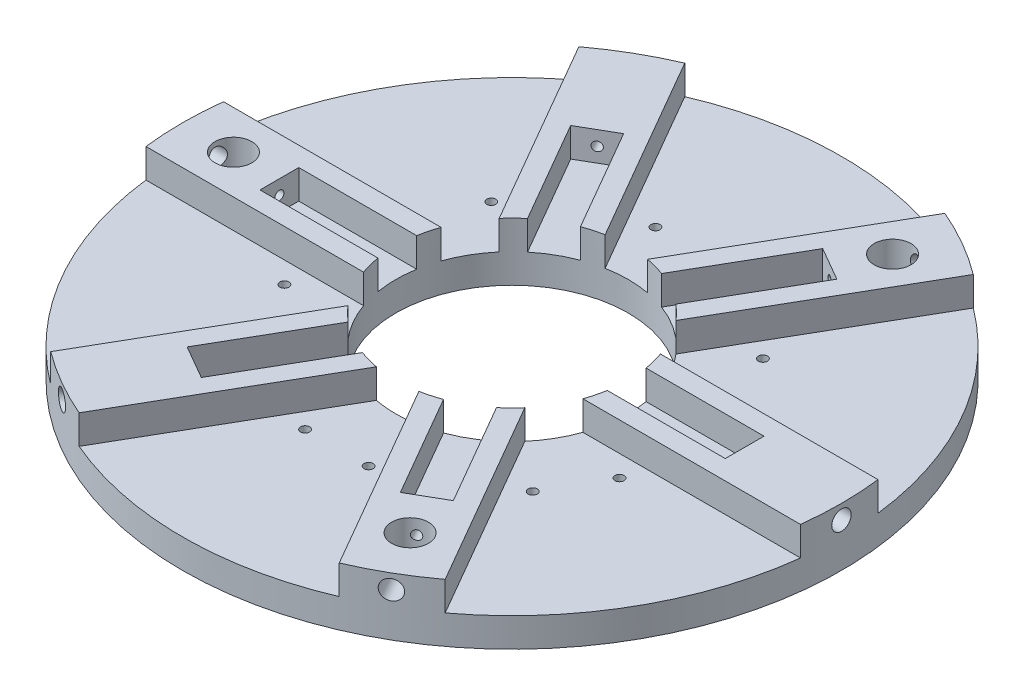
SolidWorks part; units mm, degrees
ref_plane "Front Plane" through (0, 0, 0) normal (0, 0, 1) x (1, 0, 0)
ref_plane "Top Plane" through (0, 0, 0) normal (0, 1, 0) x (1, 0, 0)
ref_plane "Right Plane" through (0, 0, 0) normal (1, 0, 0) x (0, 0, -1)
sketch "Sketch1" plane through (0, 0, 0) normal (0, 1, 0) x (1, 0, 0)
  circle A0 centre (0, 0) radius 43.18
extrude "Boss-Extrude1" add sketch "Sketch1" along normal blind 7.62 contours A0
hole_wizard "#97 (0.0059) Diameter Hole1" positions "Sketch5" profile "Sketch4" hole size "#97" standard "ANSI Inch"
sketch "Sketch5" plane through (0, 7.62, 0) normal (0, 1, 0) x (1, 0, 0)
  point P0 (0, 0)
sketch "Sketch4" plane through (0, 7.62, 0) normal (1, 0, 0) x (0, 0, 1)
  line L0 (0, 0) -> (0, 34.5571)
  line L1 (0, 34.5571) -> (15.24, 25.4)
  line L2 (15.24, 25.4) -> (15.24, 0)
  line L5 (15.24, 0) -> (0, 0)
  line L10 (0, 34.5571) -> (-15.24, 25.4) construction
  line L11 (0, -6.35) -> (0, 107.95) construction
  dimension "Hole Dia." = 30.48
  dimension "Hole Depth" = 25.4
  dimension "Drill Angle" = 118
hole_wizard "CBORE for #00 Binding Head Machine Screw1" positions "Sketch7" profile "Sketch6" counterbore size "#00" standard "ANSI Inch" end condition through all
sketch "Sketch7" plane through (0, 7.62, 0) normal (0, 1, 0) x (1, 0, 0)
  point P0 (-36.4998, 0)
sketch "Sketch6" plane through (-36.4998, 7.62, 0) normal (1, 0, 0) x (0, 0, 1)
  line L0 (0, 0) -> (0, 7.62)
  line L1 (0, 7.62) -> (1.27, 7.62)
  line L3 (1.27, 7.62) -> (1.27, 6.35)
  line L4 (1.27, 6.35) -> (2.413, 6.35)
  line L5 (2.413, 6.35) -> (2.413, 0)
  line L7 (2.413, 0) -> (0, 0)
  line L11 (0, -6.35) -> (0, 107.95) construction
  dimension "Thru Hole Dia." = 2.54
  dimension "Thru Hole Depth" = 7.62
  dimension "C'Bore Dia." = 4.826
  dimension "C'Bore Depth" = 6.35
pattern_circular "CirPattern1" count 3 over 360 about axis through (0, 0, 0) along (0, 1, 0) of "CBORE for #00 Binding Head Machine Screw1"
sketch "Sketch8" plane through (0, 7.62, 0) normal (0, 1, 0) x (1, 0, 0)
  line L0 (-14.3684, -5.08) -> (-42.8801, -5.08)
  line L1 (-11.5836, -9.9034) -> (-25.8395, -34.5953)
  arc A0 (-14.3684, -5.08) -> (-11.5836, -9.9034) centre (0, 0) ccw
  circle A1 centre (0, 0) radius 15.24 construction
  circle A2 centre (0, 0) radius 43.18 construction
  arc A3 (-42.8801, -5.08) -> (-25.8395, -34.5953) centre (0, 0) ccw
extrude "Cut-Extrude1" cut sketch "Sketch8" against normal blind 3.81
sketch "Sketch9" plane through (0, 7.62, 0) normal (0, 1, 0) x (1, 0, 0)
  line L0 (0, 0) -> (0, 2.54)
  line L1 (0, 2.54) -> (-30.48, 2.54)
  line L2 (-30.48, 2.54) -> (-30.48, -2.54)
  line L3 (-30.48, -2.54) -> (0, -2.54)
  line L4 (0, -2.54) -> (0, 0)
extrude "Cut-Extrude2" cut sketch "Sketch9" against normal blind 3.81
pattern_circular "CirPattern2" count 6 over 360 about axis through (0, 0, 0) along (0, 1, 0) of "Cut-Extrude1", "Cut-Extrude2"
ref_plane "Plane1" through (-42.8801, 0, 0) normal (1, 0, 0) x (0, 0, -1)
ref_plane "Plane2" through (-44.1501, 0, 0) normal (1, 0, 0) x (0, 0, -1)
hole_wizard "#97 (0.0059) Diameter Hole2" positions "Sketch11" profile "Sketch10" hole size "#97" standard "ANSI Inch"
sketch "Sketch11" plane through (-44.1501, 0, 0) normal (1, 0, 0) x (0, 0, -1)
  point P0 (0, 5.715)
sketch "Sketch10" plane through (-44.1501, 5.715, 0) normal (0, 1, 0) x (0, 0, 1)
  line L0 (0, 0) -> (0, 8.89)
  line L1 (0, 8.89) -> (1.27, 8.89)
  line L2 (1.27, 8.89) -> (1.27, 0)
  line L5 (1.27, 0) -> (0, 0)
  line L10 (0, 8.89) -> (-1.27, 8.89) construction
  line L11 (0, -6.35) -> (0, 107.95) construction
  dimension "Hole Dia." = 2.54
  dimension "Hole Depth" = 8.89
  dimension "Drill Angle" = 180
hole_wizard "#0-80 Tapped Hole2" positions "Sketch13" profile "Sketch12" tap size "#0-80" standard "ANSI Inch"
sketch "Sketch13" plane through (-44.1501, 0, 0) normal (1, 0, 0) x (0, 0, -1)
  point P0 (0, 5.715)
sketch "Sketch12" plane through (-44.1501, 5.715, 0) normal (0, 1, 0) x (0, 0, 1)
  line L0 (0, 0) -> (0, 21.9479)
  line L1 (0, 21.9479) -> (0.5956, 21.59)
  line L2 (0.5956, 21.59) -> (0.5956, 0)
  line L5 (0.5956, 0) -> (0, 0)
  line L10 (0, 21.9479) -> (-0.5956, 21.59) construction
  line L11 (0, -6.35) -> (0, 107.95) construction
  dimension "Tap Drill Dia." = 1.1913
  dimension "Tap Drill Depth" = 21.59
  dimension "Drill Angle" = 118
cosmetic thread "Hole Thread1" parameters "D1"=3.6815, "D2"=1.524
pattern_circular "CirPattern3" count 6 over 360 about axis through (0, 0, 0) along (0, 1, 0) of "#97 (0.0059) Diameter Hole2", "#0-80 Tapped Hole2"
hole_wizard "#0-80 Tapped Hole3" positions "Sketch15" profile "Sketch14" tap size "#0-80" standard "ANSI Inch" end condition through all
sketch "Sketch15" plane through (0, 3.81, 0) normal (0, 1, 0) x (1, 0, 0)
  line L0 (-14.3684, -5.08) -> (-42.8801, -5.08) construction
  circle A0 centre (0, 0) radius 15.24 construction
  point P0 (-21.9552, -7.8704)
  dimension "D1" = 2.7904
  dimension "D2" = 23.3233
sketch "Sketch14" plane through (-21.9552, 3.81, 7.8704) normal (1, 0, 0) x (0, 0, 1)
  line L0 (0, 0) -> (0, 3.81)
  line L1 (0, 3.81) -> (0.5956, 3.81)
  line L2 (0.5956, 3.81) -> (0.5956, 0)
  line L5 (0.5956, 0) -> (0, 0)
  line L11 (0, -6.35) -> (0, 107.95) construction
  dimension "Thru Tap Drill Dia." = 1.1913
  dimension "Thru Tap Drill Depth" = 3.81
cosmetic thread "Hole Thread2" parameters "D2"=1.524
ref_plane "Plane3" through (0, 0, 0) normal (0, 0, -1) x (-1, 0, 0)
mirror "Mirror1" about plane through (0, 0, 0) normal (0, 0, -1) of "#0-80 Tapped Hole3"
pattern_circular "CirPattern4" count 6 every 60 about axis through (0, 0, 0) along (0, 1, 0) of "Mirror1", "#0-80 Tapped Hole3"
